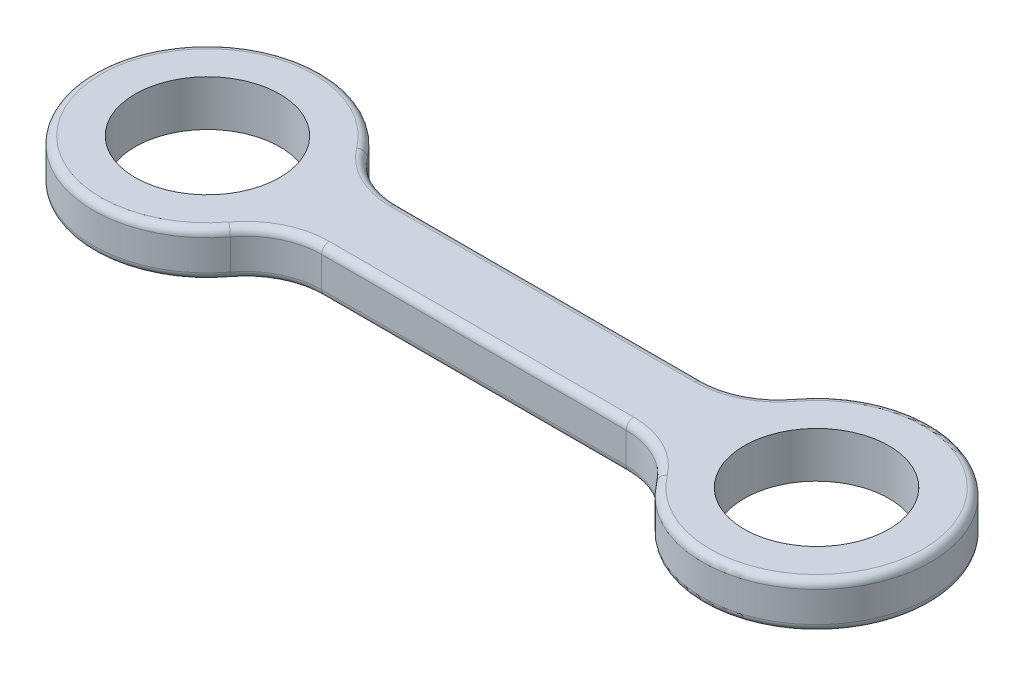
SolidWorks part; units mm, degrees
ref_plane "Front Plane" through (0, 0, 0) normal (0, 0, 1) x (1, 0, 0)
ref_plane "Top Plane" through (0, 0, 0) normal (0, 1, 0) x (1, 0, 0)
ref_plane "Right Plane" through (0, 0, 0) normal (1, 0, 0) x (0, 0, -1)
sketch "Sketch1" plane through (0, 0, 0) normal (0, 1, 0) x (1, 0, 0)
  line L1 (-28.046, 5) -> (11.954, 5)
  line L3 (-28.046, -5) -> (11.954, -5)
  circle A0 centre (-48.046, 0) radius 9.5
  circle A1 centre (31.954, 0) radius 9.5
  arc A2 (-36.046, 9) -> (-36.046, -9) centre (-48.046, 0) ccw
  arc A3 (19.954, -9) -> (19.954, 9) centre (31.954, 0) ccw
  arc A4 (19.954, 9) -> (11.954, 5) centre (11.954, 15) cw
  arc A5 (19.954, -9) -> (11.954, -5) centre (11.954, -15) ccw
  arc A6 (-28.046, -5) -> (-36.046, -9) centre (-28.046, -15) ccw
  arc A7 (-28.046, 5) -> (-36.046, 9) centre (-28.046, 15) cw
  point P6 (-48.046, 5)
  point P8 (31.954, 5)
  point P9 (-48.046, -5)
  point P10 (49.3563, -5)
  dimension "D1" = 19
  dimension "D2" = 19
  dimension "D3" = 30
  dimension "D4" = 30
  dimension "D5" = 10
  dimension "D6" = 80
  dimension "D7" = 10
extrude "Boss-Extrude1" add sketch "Sketch1" along normal blind 6
fillet "Fillet1" radius 1 16 edges at (-63.046, 0, 0) (-32.5181, 0, -6.0557) (-8.046, 0, -5) (16.4262, 0, -6.0557) (46.954, 0, 0) (16.4262, 0, 6.0557) (-8.046, 0, 5) (-32.5181, 6, 6.0557) (-63.046, 6, 0) (-32.5181, 6, -6.0557) (-8.046, 6, -5) (16.4262, 6, -6.0557) (46.954, 6, 0) (16.4262, 6, 6.0557) (-32.5181, 0, 6.0557) (-8.046, 6, 5)
